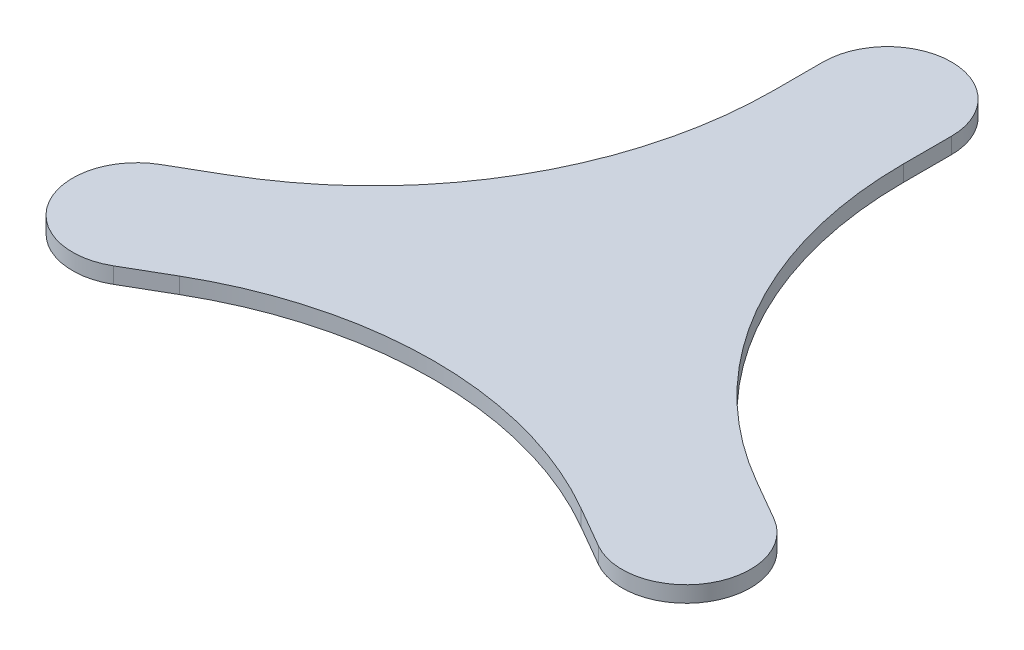
SolidWorks part; units mm, degrees
ref_plane "Front Plane" through (0, 0, 0) normal (0, 0, 1) x (1, 0, 0)
ref_plane "Top Plane" through (0, 0, 0) normal (0, 1, 0) x (1, 0, 0)
ref_plane "Right Plane" through (0, 0, 0) normal (1, 0, 0) x (0, 0, -1)
sketch "Sketch1" plane through (0, 0, 0) normal (0, 1, 0) x (1, 0, 0)
  line L0 (0, 197.5) -> (0, 0) construction
  line L1 (40, 197.5) -> (40, 167.4316)
  line L2 (-40, 197.5) -> (-40, 167.4316)
  line L3 (0, 0) -> (-171.04, -98.75) construction
  line L11 (-165, -49.0748) -> (-191.04, -64.109)
  line L12 (0, 0) -> (171.04, -98.75) construction
  line L13 (165, -49.0748) -> (191.04, -64.109)
  line L15 (-125, -118.3568) -> (-151.04, -133.391)
  line L16 (125, -118.3568) -> (151.04, -133.391)
  line L18 (0, 58.5) -> (-50.6625, 29.25)
  line L19 (-50.6625, 29.25) -> (-50.6625, -29.25)
  line L20 (-50.6625, -29.25) -> (0, -58.5)
  line L21 (0, -58.5) -> (50.6625, -29.25)
  line L22 (50.6625, -29.25) -> (50.6625, 29.25)
  line L23 (50.6625, 29.25) -> (0, 58.5)
  arc A6 (40, 197.5) -> (-40, 197.5) centre (0, 197.5) ccw
  arc A18 (-191.04, -64.109) -> (-151.04, -133.391) centre (-171.04, -98.75) ccw
  arc A20 (151.04, -133.391) -> (191.04, -64.109) centre (171.04, -98.75) ccw
  circle A21 centre (0, 197.5) radius 20
  circle A22 centre (-171.04, -98.75) radius 20
  circle A23 centre (171.04, -98.75) radius 20
  arc A24 (-40, 167.4316) -> (-165, -49.0748) centre (-290, 167.4316) cw
  arc A25 (40, 167.4316) -> (165, -49.0748) centre (290, 167.4316) ccw
  arc A26 (-125, -118.3568) -> (125, -118.3568) centre (0, -334.8632) cw
  circle A27 centre (0, 0) radius 50.6625 construction
  point P0 (0, 0)
  dimension "D1" = 40
  dimension "D2" = 120
  dimension "D3" = 120
  dimension "D4" = 40
  dimension "D7" = 250
  dimension "D8" = 117
  dimension "D9" = 139
extrude "Boss-Extrude2" add sketch "Sketch1" along normal blind 10 contours A26 L16 A20 L13 A25 L1 A6 L2 A24 L11 A18 L15
